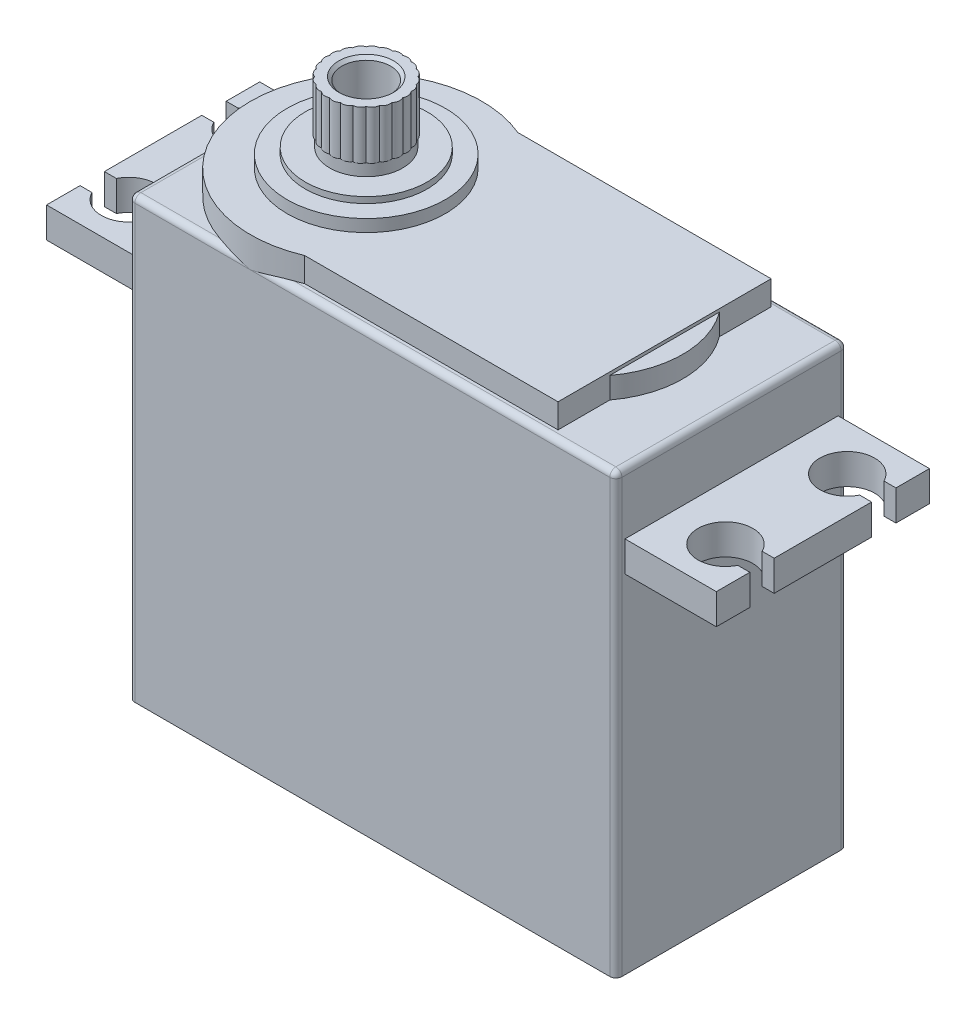
SolidWorks part; units mm, degrees
ref_plane "Alzado" through (0, 0, 0) normal (0, 0, 1) x (1, 0, 0)
ref_plane "Planta" through (0, 0, 0) normal (0, 1, 0) x (1, 0, 0)
ref_plane "Vista lateral" through (0, 0, 0) normal (1, 0, 0) x (0, 0, -1)
sketch "Croquis1" plane through (0, 0, 0) normal (0, 1, 0) x (1, 0, 0)
  line L1 (0, 0) -> (40, 0)
  line L2 (0, 0) -> (0, -19)
  line L3 (0, -19) -> (40, -19)
  line L4 (40, 0) -> (40, -19)
  dimension "D1" = 19
  dimension "D2" = 40
extrude "Saliente-Extruir1" add sketch "Croquis1" along normal blind 36
ref_plane "Plano1" through (0, 31, 0) normal (0, 1, 0) x (-1, 0, 0)
sketch "Croquis2" plane through (0, 31, 0) normal (0, 1, 0) x (-1, 0, 0)
  line L0 (-40, 19) -> (-40, 0) construction
  line L1 (-40, 18.25) -> (-47.5, 18.25)
  line L2 (-40, 18.25) -> (-40, 0.75)
  line L3 (-40, 0.75) -> (-47.5, 0.75)
  line L4 (-47.5, 18.25) -> (-47.5, 15.5)
  line L5 (-40, 0) -> (0, 0) construction
  line L8 (-20, 19) -> (-20, 0) construction
  line L9 (0, 19) -> (-40, 19) construction
  line L10 (-46.2408, 13.0745) -> (-46.5156, 13.5) construction
  line L11 (-47.5, 3.5) -> (-47.5, 0.75)
  line L12 (-46.5156, 15.5) -> (-47.5, 15.5)
  line L13 (-46.5156, 13.5) -> (-47.5, 13.5)
  line L14 (-47.5, 9.5) -> (-40, 9.5) construction
  line L16 (-46.2408, 5.9255) -> (-46.5156, 5.5) construction
  line L17 (-46.5156, 5.5) -> (-47.5, 5.5)
  line L18 (-46.5156, 3.5) -> (-47.5, 3.5)
  line L19 (-40, 0.75) -> (-47.5, 0.75)
  line L20 (-47.5, 13.5) -> (-47.5, 5.5)
  line L21 (6.2408, 5.9255) -> (6.5156, 5.5) construction
  line L22 (6.2408, 13.0745) -> (6.5156, 13.5) construction
  line L23 (7.5, 13.5) -> (7.5, 5.5)
  line L24 (0, 0.75) -> (7.5, 0.75)
  line L25 (6.5156, 3.5) -> (7.5, 3.5)
  line L26 (6.5156, 5.5) -> (7.5, 5.5)
  line L27 (6.5156, 13.5) -> (7.5, 13.5)
  line L28 (6.5156, 15.5) -> (7.5, 15.5)
  line L29 (7.5, 3.5) -> (7.5, 0.75)
  line L30 (7.5, 18.25) -> (7.5, 15.5)
  line L31 (0, 0.75) -> (7.5, 0.75)
  line L32 (0, 18.25) -> (0, 0.75)
  line L33 (0, 18.25) -> (7.5, 18.25)
  arc A0 (-46.5156, 13.5) -> (-46.5156, 15.5) centre (-44.5, 14.5) ccw
  arc A1 (-46.5156, 3.5) -> (-46.5156, 5.5) centre (-44.5, 4.5) ccw
  arc A2 (-46.5156, 5.5) -> (-46.5156, 3.5) centre (-44.5, 4.5) cw
  arc A3 (6.5156, 5.5) -> (6.5156, 3.5) centre (4.5, 4.5) ccw
  arc A4 (6.5156, 3.5) -> (6.5156, 5.5) centre (4.5, 4.5) cw
  arc A5 (6.5156, 13.5) -> (6.5156, 15.5) centre (4.5, 14.5) cw
  dimension "D6" = 4.5
  dimension "D1" = 17.5
  dimension "D2" = 0.75
  dimension "D3" = 7.5
  dimension "D4" = 3.75
  dimension "D7" = 2
  dimension "D8" = 4.5
extrude "Saliente-Extruir2" add sketch "Croquis2" against normal blind 2.5 contours A1 L18 L11 L3 L2 L1 L4 L12 A0 L13 L20 L17 | L27 A5 L28 L30 L33 L32 L24 L29 L25 A3 L26 L23
fillet "Redondeo1" radius 0.5 4 edges at (0, 18, 0) (0, 18, 19) (40, 18, 0) (40, 18, 19)
fillet "Redondeo2" radius 0.5 8 edges at (39.8536, 36, 0.1464) (39.8536, 36, 18.8536) (0.1464, 36, 18.8536) (0.1464, 36, 0.1464) (0, 36, 9.5) (20, 36, 19) (40, 36, 9.5) (20, 36, 0)
sketch "Croquis3" plane through (0, 36, 0) normal (0, 1, 0) x (1, 0, 0)
  line L1 (34.5, -0.75) -> (14.5, -0.75)
  line L2 (34.5, -0.75) -> (34.5, -18.25)
  line L3 (34.5, -18.25) -> (14.5, -18.25)
  line L5 (40, -18.25) -> (40, -0.75) construction
  line L9 (0.5, 0) -> (39.5, 0) construction
  line L11 (0, -18.25) -> (0, -0.75) construction
  line L12 (14.5, -18.25) -> (13.6997, -18.25)
  line L13 (14.5, -0.75) -> (13.6997, -0.75)
  arc A0 (13.6997, -0.75) -> (13.6997, -18.25) centre (10, -9.5) ccw
  circle A1 centre (10, -9.5) radius 9.5
  dimension "D5" = 19
  dimension "D6" = 10
  dimension "D1" = 5.5
  dimension "D2" = 17.5
  dimension "D3" = 20
  dimension "D4" = 0.75
extrude "Saliente-Extruir3" add sketch "Croquis3" along normal blind 2 contours A1 L12 L3 L2 L1 L13
sketch "Croquis4" plane through (0, 36, 0) normal (0, 1, 0) x (1, 0, 0)
  line L0 (34.5, -0.75) -> (14.5, -0.75)
  line L1 (34.5, -0.75) -> (34.5, -18.25)
  line L2 (34.5, -18.25) -> (14.5, -18.25)
  line L3 (14.5, -18.25) -> (13.6997, -18.25)
  line L4 (14.5, -0.75) -> (13.6997, -0.75)
  line L5 (34.5, -0.75) -> (34.5, -18.25) construction
  line L6 (34.5, -18.25) -> (13.6997, -18.25) construction
  arc A0 (13.6997, -0.75) -> (13.6997, -18.25) centre (10, -9.5) ccw
  circle A1 centre (10, -9.5) radius 9.5
  arc M1 (13.6997, -18.25) -> (13.6997, -0.75) centre (10, -9.5) ccw
  line M5 (39.5, -0.5) -> (0.5, -0.5)
  line M7 (0.5, -18.5) -> (39.5, -18.5)
  dimension "D1" = 20
extrude "Saliente-Extruir4" add sketch "Croquis4" along normal mid plane 4 contours A0 M7 M1 M5 | A0 M7 | A0 M5
sketch "Croquis5" plane through (0, 38, 0) normal (0, 1, 0) x (1, 0, 0)
  circle A0 centre (10, -9.5) radius 6.5
  arc A1 (6.9586, -0.5) -> (0.5, -9.5) centre (10, -9.5) ccw construction
  dimension "D1" = 13
extrude "Saliente-Extruir5" add sketch "Croquis5" along normal blind 1
sketch "Croquis6" plane through (0, 39, 0) normal (0, 1, 0) x (1, 0, 0)
  circle A0 centre (10, -9.5) radius 5
  circle A1 centre (10, -9.5) radius 6.5 construction
  dimension "D1" = 10
extrude "Saliente-Extruir6" add sketch "Croquis6" along normal blind 0.5
sketch "Croquis7" plane through (0, 39.5, 0) normal (0, 1, 0) x (1, 0, 0)
  circle A0 centre (10, -9.5) radius 3
  dimension "D1" = 6
extrude "Saliente-Extruir7" add sketch "Croquis7" along normal blind 5
sketch "Croquis8" plane through (0, 44.5, 0) normal (0, 1, 0) x (1, 0, 0)
  line L0 (6.9, -9.5) -> (7, -9.5) construction
  arc A0 (7.5406, -11.3872) -> (8.1128, -11.9594) centre (10, -9.5) ccw
  circle A1 centre (10, -9.5) radius 3 construction
  arc A2 (7, -9.5) -> (7.1022, -8.7235) centre (7.5937, -9.1832) cw
  circle A3 centre (10, -9.5) radius 3 construction
  arc A4 (7.1022, -8.7235) -> (7.4019, -8) centre (7.7577, -8.5712) cw
  arc A5 (7.4019, -8) -> (7.8787, -7.3787) centre (8.0745, -8.0225) cw
  arc A7 (10, -6.5) -> (9.2235, -6.6022) centre (9.6832, -7.0937) ccw
  arc A8 (9.2235, -6.6022) -> (8.5, -6.9019) centre (9.0712, -7.2577) ccw
  arc A9 (7.8787, -7.3787) -> (8.5, -6.9019) centre (8.5225, -7.5745) cw
  arc A10 (10, -6.5) -> (10.7765, -6.6022) centre (10.3168, -7.0937) cw
  arc A11 (10.7765, -6.6022) -> (11.5, -6.9019) centre (10.9288, -7.2577) cw
  arc A12 (12.1213, -7.3787) -> (11.5, -6.9019) centre (11.4775, -7.5745) ccw
  arc A13 (12.5981, -8) -> (12.1213, -7.3787) centre (11.9255, -8.0225) ccw
  arc A14 (12.8978, -8.7235) -> (12.5981, -8) centre (12.2423, -8.5712) ccw
  arc A15 (13, -9.5) -> (12.8978, -8.7235) centre (12.4063, -9.1832) ccw
  arc A16 (12.5981, -11) -> (12.1213, -11.6213) centre (11.9255, -10.9775) cw
  arc A17 (12.8978, -10.2765) -> (12.5981, -11) centre (12.2423, -10.4288) cw
  arc A18 (13, -9.5) -> (12.8978, -10.2765) centre (12.4063, -9.8168) cw
  arc A19 (12.1213, -11.6213) -> (11.5, -12.0981) centre (11.4775, -11.4255) cw
  arc A20 (10.7765, -12.3978) -> (11.5, -12.0981) centre (10.9288, -11.7423) ccw
  arc A21 (10, -12.5) -> (10.7765, -12.3978) centre (10.3168, -11.9063) ccw
  arc A22 (10, -12.5) -> (9.2235, -12.3978) centre (9.6832, -11.9063) cw
  arc A23 (9.2235, -12.3978) -> (8.5, -12.0981) centre (9.0712, -11.7423) cw
  arc A24 (7.8787, -11.6213) -> (8.5, -12.0981) centre (8.5225, -11.4255) ccw
  arc A25 (7.4019, -11) -> (7.8787, -11.6213) centre (8.0745, -10.9775) ccw
  arc A26 (7.1022, -10.2765) -> (7.4019, -11) centre (7.7577, -10.4288) ccw
  arc A27 (7, -9.5) -> (7.1022, -10.2765) centre (7.5937, -9.8168) ccw
  circle M1 centre (10, -9.5) radius 3
  dimension "D1" = 6.2
extrude "Saliente-Extruir8" add sketch "Croquis8" against normal blind 4 contours M1 | A9 M1 | A8 M1 | A7 M1 | A10 M1 | A11 M1 | A12 M1 | A14 M1 | A15 M1 | A13 M1 | A5 M1 | A25 M1 | A26 M1 | A27 M1 | A2 M1 | A4 M1 | A24 M1 | A23 M1 | A22 M1 | A21 M1 | A20 M1 | A19 M1 | A16 M1 | A17 M1 | A18 M1
sketch "Croquis9" plane through (0, 44.5, 0) normal (0, 1, 0) x (1, 0, 0)
  circle A0 centre (10, -9.5) radius 2
  dimension "D1" = 4
extrude "Cortar-Extruir1" cut sketch "Croquis9" against normal blind 5
chamfer "Chaflán1" distance 0.25 angle 45 1 edges at (10, 44.5, 11.5)
sketch "Croquis10" plane through (0, 36, 0) normal (0, 1, 0) x (1, 0, 0)
  line L0 (36, -9.5) -> (34.5, -9.5) construction
  line L2 (34.5, -5) -> (34.5, -14) construction
  line L3 (34.5, -5) -> (34.5, -14)
  line L6 (34.5, -0.75) -> (34.5, -18.25) construction
  line L7 (34.5, -14) -> (34.4855, -14.0527)
  arc A1 (34.5, -14) -> (34.5, -5) centre (28.5, -9.5) ccw
  line M4 (34.5, -0.75) -> (34.5, -18.25)
  dimension "D1" = 9
extrude "Saliente-Extruir9" add sketch "Croquis10" along normal blind 1.75 contours A1 M4
